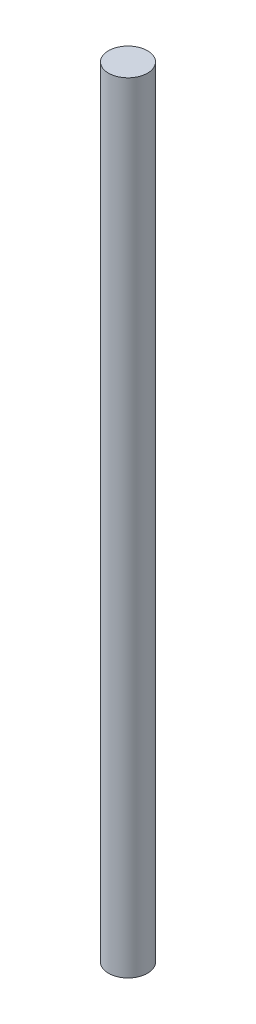
SolidWorks part; units mm, degrees
ref_plane "前视基准面" through (0, 0, 0) normal (0, 0, 1) x (1, 0, 0)
ref_plane "上视基准面" through (0, 0, 0) normal (0, 1, 0) x (1, 0, 0)
ref_plane "右视基准面" through (0, 0, 0) normal (1, 0, 0) x (0, 0, -1)
other "Configuration Table"
sketch "草图1" plane through (0, 0, 0) normal (0, 1, 0) x (1, 0, 0)
  circle A0 centre (0, 0) radius 2.5
  dimension "D1" = 5
extrude "凸台-拉伸1" add sketch "草图1" along normal blind 100
